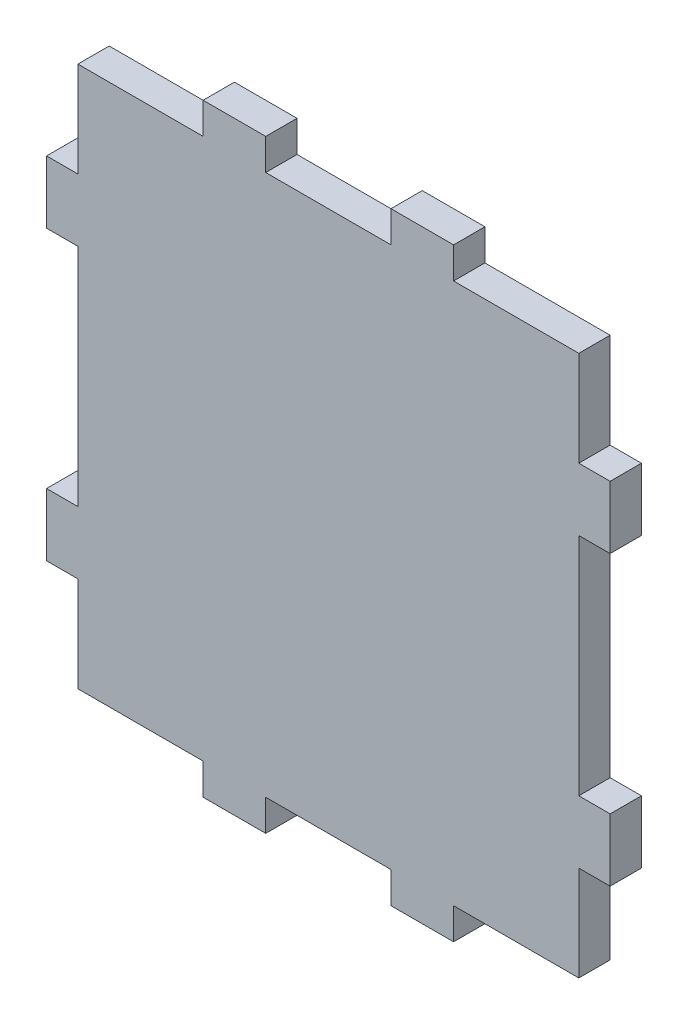
SolidWorks part; units mm, degrees
ref_plane "Front Plane" through (0, 0, 0) normal (0, 0, 1) x (1, 0, 0)
ref_plane "Top Plane" through (0, 0, 0) normal (0, 1, 0) x (1, 0, 0)
ref_plane "Right Plane" through (0, 0, 0) normal (1, 0, 0) x (0, 0, -1)
sketch "Sketch1" plane through (0, 0, 0) normal (0, 0, 1) x (1, 0, 0)
  line L0 (19.05, 0) -> (31.75, 0)
  line L1 (0, 0) -> (12.7, 0)
  line L2 (0, 0) -> (0, -9.652)
  line L3 (0, -54.864) -> (12.7, -54.864)
  line L4 (50.8, -16.002) -> (50.8, -38.862)
  line L6 (12.7, 0) -> (12.7, 3.175)
  line L7 (12.7, 3.175) -> (19.05, 3.175)
  line L8 (19.05, 0) -> (19.05, 3.175)
  line L9 (0, -16.002) -> (0, -38.862)
  line L10 (31.75, 0) -> (31.75, 3.175)
  line L11 (31.75, 3.175) -> (38.1, 3.175)
  line L12 (38.1, 0) -> (38.1, 3.175)
  line L13 (50.8, -9.652) -> (53.975, -9.652)
  line L14 (50.8, -45.212) -> (50.8, -54.864)
  line L15 (50.8, -16.002) -> (53.975, -16.002)
  line L16 (53.975, -9.652) -> (53.975, -16.002)
  line L17 (50.8, -38.862) -> (53.975, -38.862)
  line L18 (38.1, -54.864) -> (50.8, -54.864)
  line L19 (50.8, -45.212) -> (53.975, -45.212)
  line L20 (53.975, -38.862) -> (53.975, -45.212)
  line L21 (19.05, -54.864) -> (31.75, -54.864)
  line L22 (31.75, -54.864) -> (31.75, -58.039)
  line L23 (31.75, -58.039) -> (38.1, -58.039)
  line L24 (38.1, -54.864) -> (38.1, -58.039)
  line L25 (0, -45.212) -> (0, -54.864)
  line L26 (12.7, -54.864) -> (12.7, -58.039)
  line L27 (12.7, -58.039) -> (19.05, -58.039)
  line L28 (19.05, -54.864) -> (19.05, -58.039)
  line L29 (0, -45.212) -> (-3.175, -45.212)
  line L30 (38.1, 0) -> (50.8, 0)
  line L31 (0, -38.862) -> (-3.175, -38.862)
  line L32 (-3.175, -45.212) -> (-3.175, -38.862)
  line L33 (0, -16.002) -> (-3.175, -16.002)
  line L34 (50.8, 0) -> (50.8, -9.652)
  line L35 (0, -9.652) -> (-3.175, -9.652)
  line L36 (-3.175, -16.002) -> (-3.175, -9.652)
  dimension "D3" = 12.7
  dimension "D4" = 6.35
  dimension "D5" = 3.175
  dimension "D6" = 6.35
  dimension "D7" = 3.175
  dimension "D8" = 22.86
  dimension "D9" = 3.175
  dimension "D10" = 6.35
  dimension "D11" = 3.175
  dimension "D12" = 3.175
  dimension "D13" = 6.35
  dimension "D14" = 9.652
  dimension "D15" = 6.35
  dimension "D16" = 3.175
  dimension "D17" = 12.7
  dimension "D18" = 6.35
  dimension "D19" = 12.7
  dimension "D20" = 3.175
  dimension "D21" = 3.175
  dimension "D22" = 6.35
  dimension "D23" = 9.652
  dimension "D24" = 9.652
  dimension "D25" = 6.35
  dimension "D26" = 9.652
  dimension "D27" = 3.175
  dimension "D28" = 12.7
  dimension "D29" = 12.7
  dimension "D30" = 22.86
extrude "Boss-Extrude1" add sketch "Sketch1" along normal blind 3.175 contours L36 L33 L2 L31 L32 L29 L3 L26 L27 L28 L22 L23 L24 L4 L19 L20 L17 L15 L16 L13 L1 L12 L11 L10 L8 L7 L6 L35
